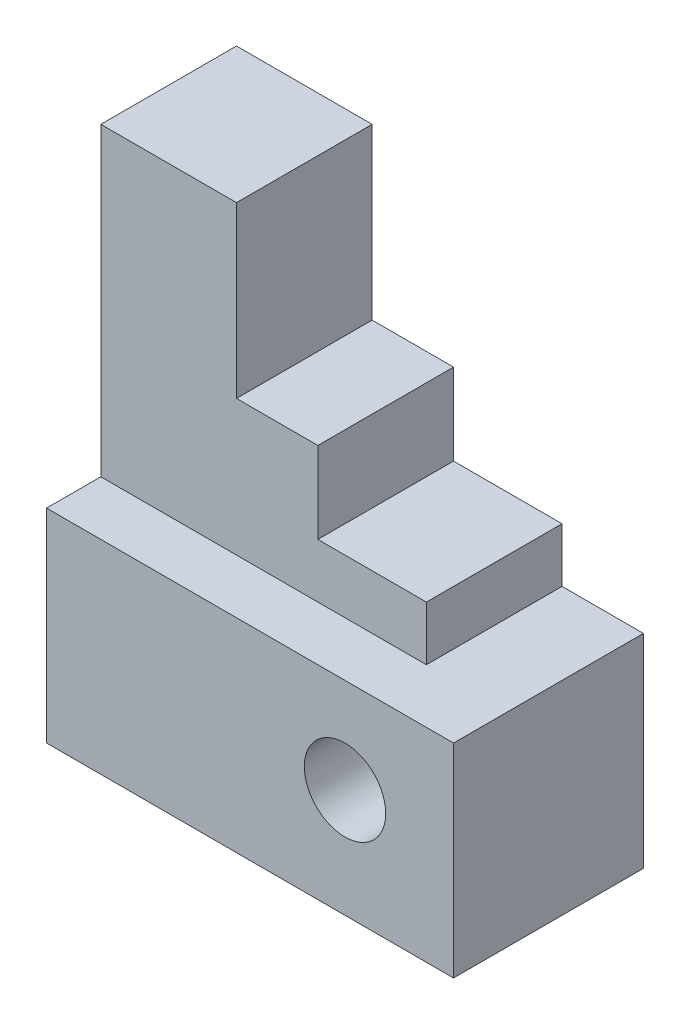
SolidWorks part; units mm, degrees
material "Aluminum Bronze"
ref_plane "Front Plane" through (0, 0, 0) normal (0, 0, 1) x (1, 0, 0)
ref_plane "Top Plane" through (0, 0, 0) normal (0, 1, 0) x (1, 0, 0)
ref_plane "Right Plane" through (0, 0, 0) normal (1, 0, 0) x (0, 0, -1)
sketch "Sketch1" plane through (0, 0, 0) normal (0, 1, 0) x (1, 0, 0)
  line L1 (0, 0) -> (60, 0)
  line L2 (0, 0) -> (0, 28)
  line L3 (0, 28) -> (60, 28)
  line L4 (60, 0) -> (60, 28)
  dimension "D1" = 28
  dimension "D2" = 60
extrude "Boss-Extrude1" add sketch "Sketch1" along normal blind 75
sketch "Sketch2" plane through (0, 75, 0) normal (0, 1, 0) x (1, 0, 0)
  line L5 (0, 0) -> (60, 0) construction
  line L14 (60, 28) -> (48, 28)
  line L15 (60, 28) -> (60, 0)
  line L16 (60, 0) -> (48, 0)
  line L17 (48, 28) -> (48, 8)
  line L19 (0, 0) -> (48, 0)
  line L20 (0, 0) -> (0, 8)
  line L21 (0, 8) -> (48, 8)
  dimension "D1" = 12
  dimension "D2" = 8
extrude "Cut-Extrude1" cut sketch "Sketch2" against normal blind 45
sketch "Sketch3" plane through (0, 0, -8) normal (0, 0, 1) x (1, 0, 0)
  line L0 (0, 75) -> (20, 75)
  line L1 (48, 75) -> (0, 75) construction
  line L2 (48, 30) -> (48, 75) construction
  line L3 (32, 38) -> (48, 38)
  line L4 (32, 38) -> (32, 50)
  line L6 (32, 50) -> (20, 50)
  line L8 (20, 50) -> (20, 75)
  line L9 (0, 30) -> (60, 30) construction
  line L10 (20, 75) -> (48, 75)
  line L11 (48, 75) -> (48, 38)
  line L12 (0, 0) -> (60, 0) construction
  line L13 (60, 30) -> (60, 0) construction
  circle A0 centre (44, 16) radius 6
  line M6 (48, 75) -> (0, 75)
  line M9 (48, 30) -> (48, 75)
  dimension "D5" = 12
  dimension "D1" = 20
  dimension "D2" = 12
  dimension "D3" = 12
  dimension "D4" = 20
  dimension "D6" = 16
  dimension "D7" = 16
extrude "Cut-Extrude2" cut sketch "Sketch3" against normal through all and the other way through all contours L8 L6 L4 L3 M9 M6 | A0
